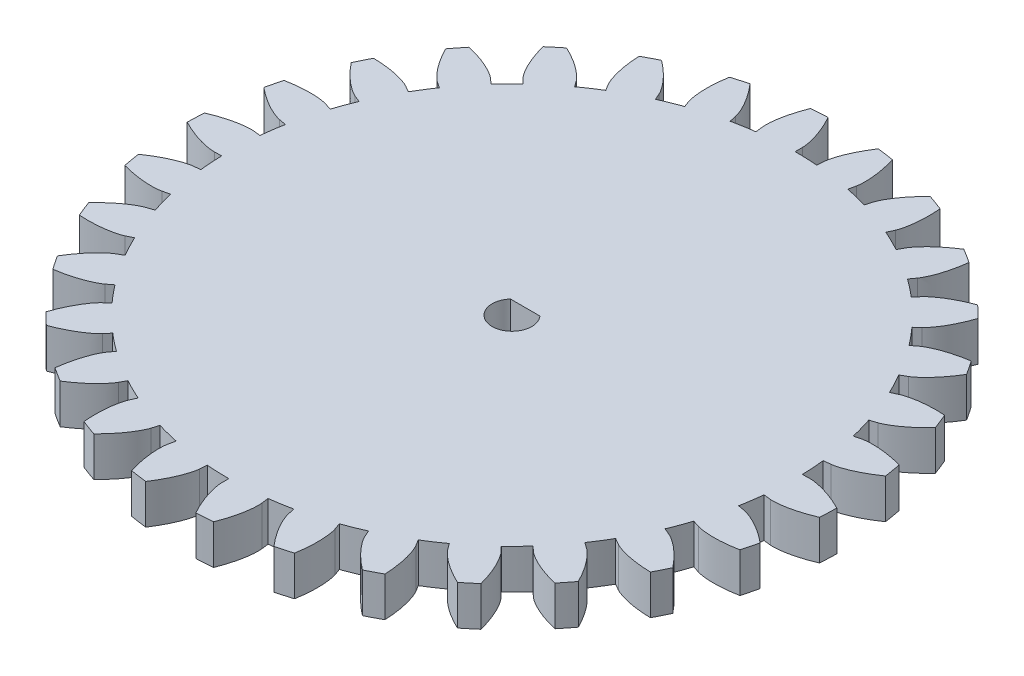
SolidWorks part; units mm, degrees
ref_plane "Front Plane" through (0, 0, 0) normal (0, 0, 1) x (1, 0, 0)
ref_plane "Top Plane" through (0, 0, 0) normal (0, 1, 0) x (1, 0, 0)
ref_plane "Right Plane" through (0, 0, 0) normal (1, 0, 0) x (0, 0, -1)
sketch "Reference attributes" plane through (0, 0, 0) normal (0, 1, 0) x (1, 0, 0)
  line L0 (0, 0) -> (30, 0) construction
  line L1 (0, -10) -> (1.56, -10) construction
  line L2 (0, 0) -> (28.9778, 7.7646) construction
  line L3 (0, 0) -> (28.1908, 10.2606) construction
  dimension "Teeth" = 30
  dimension "Module" = 1.56
  dimension "D2" = 10
  dimension "Helix Angle" = 15
  dimension "Pressure angle" = 20
sketch "Gear billet" plane through (0, 0, 0) normal (0, 1, 0) x (1, 0, 0)
  circle A0 centre (0, 0) radius 24.96
  dimension "OuterDi" = 49.92
extrude "Gear billet Extrude" add sketch "Gear billet" along normal blind 3
ref_plane "Opposite gear face" through (0, 3, 0) normal (0, 1, 0) x (1, 0, 0)
ref_point "Twist centre point top"
ref_point "Twist centre point bottom"
ref_axis "Axis" through (0, 3, 0) along (0, -1, 0)
sketch "Involute Profile" plane through (0, 3, 0) normal (0, 1, 0) x (1, 0, 0)
  line L0 (0, 0) -> (0, 21.9888) construction
  line L1 (0, 0) -> (1.7393, 21.9199) construction
  circle A0 centre (0, 0) radius 23.4
  circle A4 centre (0, 0) radius 21.9888 construction
  spline S0 degree 4 poles (0, 21.9888) (0, 22.0227) (-0.002, 22.0904) (-0.0183, 22.28) (-0.0768, 22.638) (-0.2134, 23.1773) (-0.4715, 23.897) (-0.8867, 24.788) (-1.4705, 25.7809) (-2.2091, 26.8084) (-3.0996, 27.8414) (-4.0685, 28.8009) (-5.1038, 29.688) (-6.2499, 30.5444) (-7.7363, 31.5083) (-9.5978, 32.5098) (-11.8594, 33.4668) (-14.465, 34.2773) (-17.1335, 34.8452) (-19.8405, 35.1813) (-22.5656, 35.2961) (-25.2912, 35.1997) (-27.663, 34.9395) (-29.6787, 34.5969) (-31.3427, 34.2349) (-32.4991, 33.942) (-33.4813, 33.6643) (-34.2972, 33.414) (-34.9416, 33.2053) (-35.5928, 32.9818) (-36.2216, 32.756) (-36.8226, 32.5279) (-37.3087, 32.3371) (-37.8607, 32.1112) (-38.2165, 31.9615) (-38.789, 31.7141) (-39.2308, 31.5139) (-39.7658, 31.2673) (-40.2388, 31.0393) (-40.7468, 30.7895) (-41.2252, 30.5448) (-41.5991, 30.3497) (-41.8363, 30.2223) (-41.9593, 30.1561) knots 0 0 0 0 0 0.002802 0.005604 0.015718 0.02996 0.048734 0.068727 0.096889 0.125051 0.153212 0.181374 0.209535 0.237696 0.271429 0.327752 0.384075 0.440398 0.496721 0.553044 0.609367 0.66569 0.722013 0.750174 0.778336 0.806497 0.820578 0.834659 0.84874 0.86282 0.876901 0.890982 0.900036 0.909091 0.920455 0.931818 0.943182 0.954545 0.965909 0.977273 0.988636 1 1 1 1 1 construction
  spline S1 degree 4 poles (0, 21.9888) (0, 22.0227) (-0.002, 22.0904) (-0.0183, 22.28) (-0.0768, 22.638) (-0.2134, 23.1773) (-0.4715, 23.897) (-0.8867, 24.788) (-1.4705, 25.7809) (-2.2091, 26.8084) (-3.0996, 27.8414) (-4.0685, 28.8009) (-5.1038, 29.688) (-6.2499, 30.5444) (-7.7363, 31.5083) (-9.5978, 32.5098) (-11.8594, 33.4668) (-14.465, 34.2773) (-17.1335, 34.8452) (-19.8405, 35.1813) (-22.5656, 35.2961) (-25.2912, 35.1997) (-27.663, 34.9395) (-29.6787, 34.5969) (-31.3427, 34.2349) (-32.4991, 33.942) (-33.4813, 33.6643) (-34.2972, 33.414) (-34.9416, 33.2053) (-35.5928, 32.9818) (-36.2216, 32.756) (-36.8226, 32.5279) (-37.3087, 32.3371) (-37.7167, 32.1701) (-37.9021, 32.0931) (-37.9939, 32.0546) knots 0 0 0 0 0 0.002802 0.005604 0.015718 0.02996 0.048734 0.068727 0.096889 0.125051 0.153212 0.181374 0.209535 0.237696 0.271429 0.327752 0.384075 0.440398 0.496721 0.553044 0.609367 0.66569 0.722013 0.750174 0.778336 0.806497 0.820578 0.834659 0.84874 0.86282 0.876901 0.890982 0.900036 0.909091 0.909091 0.909091 0.909091 0.909091
  spline S2 degree 4 poles (1.7393, 21.9199) (1.742, 21.9537) (1.7493, 22.0211) (1.7806, 22.2087) (1.8672, 22.561) (2.046, 23.0878) (2.3602, 23.7848) (2.8446, 24.6402) (3.5051, 25.5838) (4.3226, 26.5496) (5.2921, 27.509) (6.3339, 28.3888) (7.4361, 29.1913) (8.6463, 29.9544) (10.2043, 30.7977) (12.1392, 31.6487) (14.4694, 32.4239) (17.131, 33.0257) (19.836, 33.3808) (22.5612, 33.5017) (25.2867, 33.4006) (27.9962, 33.0889) (30.34, 32.6419) (32.3223, 32.141) (33.9524, 31.6485) (35.082, 31.2651) (36.0392, 30.9106) (36.8327, 30.5965) (37.4586, 30.3374) (38.0901, 30.0632) (38.699, 29.7884) (39.2801, 29.5134) (39.7496, 29.2848) (40.282, 29.0159) (40.6248, 28.8385) (41.176, 28.5466) (41.6005, 28.3121) (42.1144, 28.0239) (42.5679, 27.7593) (43.0545, 27.4701) (43.5121, 27.1883) (43.8694, 26.9642) (44.0957, 26.8185) (44.2131, 26.7428) knots 0 0 0 0 0 0.002802 0.005604 0.015718 0.02996 0.048734 0.068727 0.096889 0.125051 0.153212 0.181374 0.209535 0.237696 0.271429 0.327752 0.384075 0.440398 0.496721 0.553044 0.609367 0.66569 0.722013 0.750174 0.778336 0.806497 0.820578 0.834659 0.84874 0.86282 0.876901 0.890982 0.900036 0.909091 0.920455 0.931818 0.943182 0.954545 0.965909 0.977273 0.988636 1 1 1 1 1 construction
  spline S3 degree 4 poles (1.7393, 21.9199) (1.742, 21.9537) (1.7493, 22.0211) (1.7806, 22.2087) (1.8672, 22.561) (2.046, 23.0878) (2.3602, 23.7848) (2.8446, 24.6402) (3.5051, 25.5838) (4.3226, 26.5496) (5.2921, 27.509) (6.3339, 28.3888) (7.4361, 29.1913) (8.6463, 29.9544) (10.2043, 30.7977) (12.1392, 31.6487) (14.4694, 32.4239) (17.131, 33.0257) (19.836, 33.3808) (22.5612, 33.5017) (25.2867, 33.4006) (27.9962, 33.0889) (30.34, 32.6419) (32.3223, 32.141) (33.9524, 31.6485) (35.082, 31.2651) (36.0392, 30.9106) (36.8327, 30.5965) (37.4586, 30.3374) (38.0901, 30.0632) (38.699, 29.7884) (39.2801, 29.5134) (39.7496, 29.2848) (40.1431, 29.086) (40.3219, 28.9946) (40.4103, 28.9489) knots 0 0 0 0 0 0.002802 0.005604 0.015718 0.02996 0.048734 0.068727 0.096889 0.125051 0.153212 0.181374 0.209535 0.237696 0.271429 0.327752 0.384075 0.440398 0.496721 0.553044 0.609367 0.66569 0.722013 0.750174 0.778336 0.806497 0.820578 0.834659 0.84874 0.86282 0.876901 0.890982 0.900036 0.909091 0.909091 0.909091 0.909091 0.909091
  point P6 (-0.3003, 23.3981)
  point P11 (2.1501, 23.301)
  dimension "BaseDi" = 43.9776
  dimension "Adjusted Reference Diameter" = 46.8
  dimension "Reference Circumferential pitch" = 2.4504
sketch "Tooth profile" plane through (0, 3, 0) normal (0, 1, 0) x (1, 0, 0)
  line L0 (0, 0) -> (0, 21.9888) construction
  line L1 (0, 0) -> (1.7393, 21.9199) construction
  line L2 (0, 0) -> (0, 21.9888)
  line L3 (0, 0) -> (1.7393, 21.9199)
  line L4 (-0.2, -5.0491) -> (-0.2, 21.9888) construction
  line L5 (-0.2, -5.0491) -> (1.9386, 21.9041) construction
  circle A0 centre (0, 0) radius 24.96 construction
  circle A1 centre (0, 0) radius 24.96
  circle A2 centre (0, 0) radius 21.45
  spline S0 degree 1 poles (-0.2, 21.9888) (-37.9165, 31.8702) knots 0 0 1 1 construction
  spline S1 degree 4 poles (999.1982, -17.1121) (-36.277, 17.6441) (-0.8293, 18.6178) (0.2518, 20.6259) (-0.0768, 22.638) (-0.2134, 23.1773) (-0.4715, 23.897) (-0.8867, 24.788) (-1.4705, 25.7809) (-2.2091, 26.8084) (-3.0996, 27.8414) (-4.0685, 28.8009) (-5.1038, 29.688) (-6.2499, 30.5444) (-7.7363, 31.5083) (-9.5978, 32.5098) (-11.8594, 33.4668) (-14.465, 34.2773) (-17.1335, 34.8452) (-19.8405, 35.1813) (-22.5656, 35.2961) (-25.2912, 35.1997) (-27.663, 34.9395) (-29.6787, 34.5969) (-31.3427, 34.2349) (-32.4991, 33.942) (-33.4813, 33.6643) (-34.2972, 33.414) (-34.9416, 33.2053) (-35.5928, 32.9818) (-36.2216, 32.756) (-36.8226, 32.5279) (-38.6811, 31.7987) (-42.1779, 30.2496) (-10.1825, 43.4984) (-959.7925, -355.2431) knots -0.138436 -0.138436 -0.138436 -0.138436 -0.138436 0.002802 0.005604 0.015718 0.02996 0.048734 0.068727 0.096889 0.125051 0.153212 0.181374 0.209535 0.237696 0.271429 0.327752 0.384075 0.440398 0.496721 0.553044 0.609367 0.66569 0.722013 0.750174 0.778336 0.806497 0.820578 0.834659 0.84874 0.86282 0.876901 0.890982 0.900036 1.039722 1.039722 1.039722 1.039722 1.039722 only from (0, 21.9888) to (-37.9939, 32.0546) construction
  spline S2 degree 4 poles (-997.4211, 61.976) (37.5589, 14.7194) (2.2993, 18.4939) (1.3805, 20.5812) (1.8672, 22.561) (2.046, 23.0878) (2.3602, 23.7848) (2.8446, 24.6402) (3.5051, 25.5838) (4.3226, 26.5496) (5.2921, 27.509) (6.3339, 28.3888) (7.4361, 29.1913) (8.6463, 29.9544) (10.2043, 30.7977) (12.1392, 31.6487) (14.4694, 32.4239) (17.131, 33.0257) (19.836, 33.3808) (22.5612, 33.5017) (25.2867, 33.4006) (27.9962, 33.0889) (30.34, 32.6419) (32.3223, 32.141) (33.9524, 31.6485) (35.082, 31.2651) (36.0392, 30.9106) (36.8327, 30.5965) (37.4586, 30.3374) (38.0901, 30.0632) (38.699, 29.7884) (39.2801, 29.5134) (41.0751, 28.6395) (44.4385, 26.8186) (13.5912, 42.5567) (928.6863, -430.0476) knots -0.138436 -0.138436 -0.138436 -0.138436 -0.138436 0.002802 0.005604 0.015718 0.02996 0.048734 0.068727 0.096889 0.125051 0.153212 0.181374 0.209535 0.237696 0.271429 0.327752 0.384075 0.440398 0.496721 0.553044 0.609367 0.66569 0.722013 0.750174 0.778336 0.806497 0.820578 0.834659 0.84874 0.86282 0.876901 0.890982 0.900036 1.039722 1.039722 1.039722 1.039722 1.039722 only from (1.7393, 21.9199) to (40.4103, 28.9489) construction
  spline S3 degree 1 poles (1.9386, 21.9041) (40.3186, 28.7712) knots 0 0 1 1 construction
  spline S4 degree 4 poles (0, 21.9888) (0, 22.0227) (-0.002, 22.0904) (-0.0183, 22.28) (-0.0768, 22.638) (-0.2134, 23.1773) (-0.4715, 23.897) (-0.8867, 24.788) (-1.4705, 25.7809) (-2.2091, 26.8084) (-3.0996, 27.8414) (-4.0685, 28.8009) (-5.1038, 29.688) (-6.2499, 30.5444) (-7.7363, 31.5083) (-9.5978, 32.5098) (-11.8594, 33.4668) (-14.465, 34.2773) (-17.1335, 34.8452) (-19.8405, 35.1813) (-22.5656, 35.2961) (-25.2912, 35.1997) (-27.663, 34.9395) (-29.6787, 34.5969) (-31.3427, 34.2349) (-32.4991, 33.942) (-33.4813, 33.6643) (-34.2972, 33.414) (-34.9416, 33.2053) (-35.5928, 32.9818) (-36.2216, 32.756) (-36.8226, 32.5279) (-37.3087, 32.3371) (-37.7167, 32.1701) (-37.9021, 32.0931) (-37.9939, 32.0546) knots 0 0 0 0 0 0.002802 0.005604 0.015718 0.02996 0.048734 0.068727 0.096889 0.125051 0.153212 0.181374 0.209535 0.237696 0.271429 0.327752 0.384075 0.440398 0.496721 0.553044 0.609367 0.66569 0.722013 0.750174 0.778336 0.806497 0.820578 0.834659 0.84874 0.86282 0.876901 0.890982 0.900036 0.909091 0.909091 0.909091 0.909091 0.909091
  spline S5 degree 4 poles (1.7393, 21.9199) (1.742, 21.9537) (1.7493, 22.0211) (1.7806, 22.2087) (1.8672, 22.561) (2.046, 23.0878) (2.3602, 23.7848) (2.8446, 24.6402) (3.5051, 25.5838) (4.3226, 26.5496) (5.2921, 27.509) (6.3339, 28.3888) (7.4361, 29.1913) (8.6463, 29.9544) (10.2043, 30.7977) (12.1392, 31.6487) (14.4694, 32.4239) (17.131, 33.0257) (19.836, 33.3808) (22.5612, 33.5017) (25.2867, 33.4006) (27.9962, 33.0889) (30.34, 32.6419) (32.3223, 32.141) (33.9524, 31.6485) (35.082, 31.2651) (36.0392, 30.9106) (36.8327, 30.5965) (37.4586, 30.3374) (38.0901, 30.0632) (38.699, 29.7884) (39.2801, 29.5134) (39.7496, 29.2848) (40.1431, 29.086) (40.3219, 28.9946) (40.4103, 28.9489) knots 0 0 0 0 0 0.002802 0.005604 0.015718 0.02996 0.048734 0.068727 0.096889 0.125051 0.153212 0.181374 0.209535 0.237696 0.271429 0.327752 0.384075 0.440398 0.496721 0.553044 0.609367 0.66569 0.722013 0.750174 0.778336 0.806497 0.820578 0.834659 0.84874 0.86282 0.876901 0.890982 0.900036 0.909091 0.909091 0.909091 0.909091 0.909091
  spline S6 degree 3 poles (-37.9165, 31.8702) (-34.5637, 33.2771) (-29.2333, 34.7703) (-21.9373, 35.188) (-16.4816, 34.6386) (-11.2068, 33.1415) (-7.1485, 31.0333) (-4.2854, 28.7886) (-2.4032, 26.8185) (-1.144, 24.9283) (-0.5176, 23.4861) (-0.2764, 22.622) (-0.2, 22.203) (-0.2, 21.9888) knots 0 0 0 0 0.227273 0.340909 0.454545 0.568182 0.681818 0.738636 0.795455 0.852273 0.880682 0.894886 0.909091 0.909091 0.909091 0.909091 construction
  spline S7 degree 3 poles (1.9386, 21.9041) (1.9556, 22.1176) (2.0649, 22.5293) (2.3737, 23.3716) (3.1122, 24.7598) (4.5169, 26.5444) (6.5491, 28.3595) (9.5808, 30.3707) (13.7931, 32.1512) (19.1698, 33.2264) (24.6519, 33.3426) (31.892, 32.3491) (37.0876, 30.439) (40.3186, 28.7712) knots 0 0 0 0 0.014205 0.028409 0.056818 0.113636 0.170455 0.227273 0.340909 0.454545 0.568182 0.681818 0.909091 0.909091 0.909091 0.909091 construction
  dimension "RootDi" = 42.9
  dimension "Offset" = 0.2
extrude "Cut tooth profile" cut sketch "Tooth profile" against normal up to next
sketch "Tooth profile OFFSET" plane through (0, 3, 0) normal (0, 1, 0) x (1, 0, 0)
  line L4 (-0.1, -2.5246) -> (-0.1, 21.9888)
  line L5 (1.839, 21.912) -> (-0.1, -2.5246)
  line L6 (-0.1, -2.5246) -> (-0.1, 21.9888)
  line L7 (1.839, 21.912) -> (-0.1, -2.5246)
  circle A3 centre (0, 0) radius 24.96 construction
  circle A4 centre (0, 0) radius 24.96
  circle A6 centre (0, 0) radius 21.35
  circle A7 centre (0, 0) radius 21.35
  spline S4 degree 3 poles (1814.9164, -893.4497) (11.2099, 41.5431) (47.43, 25.2825) (39.9677, 29.0624) (39.857, 29.118) (39.5391, 29.276) (39.3439, 29.3707) (38.9333, 29.5665) (38.7217, 29.6655) (38.306, 29.8557) (38.0998, 29.9479) (37.053, 30.4066) (36.203, 30.7469) (33.6257, 31.6798) (31.8646, 32.1874) (28.2886, 32.9442) (26.4731, 33.1936) (22.8249, 33.4041) (20.9921, 33.3652) (17.3608, 32.9668) (15.562, 32.6072) (12.0726, 31.5326) (10.3808, 30.8175) (8.0112, 29.4496) (7.2497, 28.9445) (5.8069, 27.8305) (5.1252, 27.2218) (3.8784, 25.8951) (3.3115, 25.1772) (2.6029, 24.0143) (2.3903, 23.6123) (2.1256, 22.9877) (2.0464, 22.776) (1.9476, 22.4534) (1.918, 22.3451) (0.4034, 15.6952) (12.5067, 9.1011) (1949.2716, 476.354) knots -0.54262 -0.54262 -0.54262 -0.54262 0.007812 0.007812 0.015625 0.015625 0.03125 0.03125 0.046875 0.046875 0.0625 0.0625 0.125 0.125 0.25 0.25 0.375 0.375 0.5 0.5 0.625 0.625 0.75 0.75 0.8125 0.8125 0.875 0.875 0.9375 0.9375 0.96875 0.96875 0.984375 0.984375 0.992187 0.992187 1.461818 1.461818 1.461818 1.461818 only from (40.3645, 28.8601) to (1.839, 21.912)
  spline S5 degree 3 poles (-1905.5571, 629.0682) (-11.748, 10.0617) (0.8394, 15.6778) (-0.1445, 22.4268) (-0.1655, 22.5371) (-0.2385, 22.8665) (-0.3007, 23.0838) (-0.5151, 23.7274) (-0.6952, 24.1449) (-1.3097, 25.3602) (-1.818, 26.1208) (-2.956, 27.5419) (-3.5873, 28.2027) (-4.9375, 29.4272) (-5.6567, 29.991) (-7.9107, 31.542) (-9.5406, 32.3887) (-12.9341, 33.736) (-14.6989, 34.2367) (-18.2872, 34.9211) (-20.1112, 35.1048) (-23.7646, 35.1836) (-25.5942, 35.0786) (-29.2188, 34.607) (-31.0145, 34.2403) (-33.6576, 33.5142) (-34.5318, 33.2422) (-35.6116, 32.8677) (-35.8244, 32.7921) (-36.2539, 32.6354) (-36.4727, 32.5534) (-36.8975, 32.3907) (-37.0995, 32.3118) (-37.429, 32.1793) (-37.5437, 32.1327) (-45.2816, 28.9549) (-7.889, 42.2995) (-1879.8826, -747.087) knots -0.461823 -0.461823 -0.461823 -0.461823 0.007812 0.007812 0.015625 0.015625 0.03125 0.03125 0.0625 0.0625 0.125 0.125 0.1875 0.1875 0.25 0.25 0.375 0.375 0.5 0.5 0.625 0.625 0.75 0.75 0.875 0.875 0.9375 0.9375 0.953125 0.953125 0.96875 0.96875 0.984375 0.984375 0.992188 0.992188 1.542618 1.542618 1.542618 1.542618 only from (-0.1, 21.9888) to (-37.9552, 31.9624)
  spline S6 degree 3 poles (40.3645, 28.8601) (40.2722, 28.9077) (40.1765, 28.9566) (39.9677, 29.0624) (39.857, 29.118) (39.5391, 29.276) (39.3439, 29.3707) (38.9333, 29.5665) (38.7217, 29.6655) (38.306, 29.8557) (38.0998, 29.9479) (37.053, 30.4066) (36.203, 30.7469) (33.6257, 31.6798) (31.8646, 32.1874) (28.2886, 32.9442) (26.4731, 33.1936) (22.8249, 33.4041) (20.9921, 33.3652) (17.3608, 32.9668) (15.562, 32.6072) (12.0726, 31.5326) (10.3808, 30.8175) (8.0112, 29.4496) (7.2497, 28.9445) (5.8069, 27.8305) (5.1252, 27.2218) (3.8784, 25.8951) (3.3115, 25.1772) (2.6029, 24.0143) (2.3903, 23.6123) (2.1256, 22.9877) (2.0464, 22.776) (1.9476, 22.4534) (1.918, 22.3451) (1.8684, 22.1275) (1.8474, 22.0187) (1.839, 21.912) knots 0 0 0 0 0.007812 0.007812 0.015625 0.015625 0.03125 0.03125 0.046875 0.046875 0.0625 0.0625 0.125 0.125 0.25 0.25 0.375 0.375 0.5 0.5 0.625 0.625 0.75 0.75 0.8125 0.8125 0.875 0.875 0.9375 0.9375 0.96875 0.96875 0.984375 0.984375 0.992187 0.992187 1 1 1 1
  spline S7 degree 3 poles (-0.1, 21.9888) (-0.1, 22.0958) (-0.1123, 22.206) (-0.1445, 22.4268) (-0.1655, 22.5371) (-0.2385, 22.8665) (-0.3007, 23.0838) (-0.5151, 23.7274) (-0.6952, 24.1449) (-1.3097, 25.3602) (-1.818, 26.1208) (-2.956, 27.5419) (-3.5873, 28.2027) (-4.9375, 29.4272) (-5.6567, 29.991) (-7.9107, 31.542) (-9.5406, 32.3887) (-12.9341, 33.736) (-14.6989, 34.2367) (-18.2872, 34.9211) (-20.1112, 35.1048) (-23.7646, 35.1836) (-25.5942, 35.0786) (-29.2188, 34.607) (-31.0145, 34.2403) (-33.6576, 33.5142) (-34.5318, 33.2422) (-35.6116, 32.8677) (-35.8244, 32.7921) (-36.2539, 32.6354) (-36.4727, 32.5534) (-36.8975, 32.3907) (-37.0995, 32.3118) (-37.429, 32.1793) (-37.5437, 32.1327) (-37.7603, 32.0437) (-37.8595, 32.0026) (-37.9552, 31.9624) knots 0 0 0 0 0.007812 0.007812 0.015625 0.015625 0.03125 0.03125 0.0625 0.0625 0.125 0.125 0.1875 0.1875 0.25 0.25 0.375 0.375 0.5 0.5 0.625 0.625 0.75 0.75 0.875 0.875 0.9375 0.9375 0.953125 0.953125 0.96875 0.96875 0.984375 0.984375 0.992188 0.992188 1 1 1 1
  line M3 (0, 21.45) -> (0, 21.9888)
  spline M4 degree 4 poles (0, 21.9888) (0, 22.0227) (-0.002, 22.0904) (-0.0183, 22.28) (-0.0768, 22.638) (-0.2134, 23.1773) (-0.4715, 23.897) (-0.8867, 24.788) (-1.4705, 25.7809) (-2.2091, 26.8084) (-3.0996, 27.8414) (-4.0685, 28.8009) (-5.1038, 29.688) (-6.2499, 30.5444) (-7.7363, 31.5083) (-9.5978, 32.5098) (-11.8594, 33.4668) (-14.465, 34.2773) (-17.1335, 34.8452) (-19.8405, 35.1813) (-22.5656, 35.2961) (-25.2912, 35.1997) (-27.663, 34.9395) (-29.6787, 34.5969) (-31.3427, 34.2349) (-32.4991, 33.942) (-33.4813, 33.6643) (-34.2972, 33.414) (-34.9416, 33.2053) (-35.5928, 32.9818) (-36.2216, 32.756) (-36.8226, 32.5279) (-37.3087, 32.3371) (-37.7167, 32.1701) (-37.9021, 32.0931) (-37.9939, 32.0546) knots 0 0 0 0 0 0.002802 0.005604 0.015718 0.02996 0.048734 0.068727 0.096889 0.125051 0.153212 0.181374 0.209535 0.237696 0.271429 0.327752 0.384075 0.440398 0.496721 0.553044 0.609367 0.66569 0.722013 0.750174 0.778336 0.806497 0.820578 0.834659 0.84874 0.86282 0.876901 0.890982 0.900036 0.909091 0.909091 0.909091 0.909091 0.909091 only from (0, 21.9888) to (-0.9929, 24.9402)
  arc M5 (-0.9929, 24.9402) -> (2.9625, 24.7836) centre (0, 0) ccw
  spline M6 degree 4 poles (40.4103, 28.9489) (40.3219, 28.9946) (40.1431, 29.086) (39.7496, 29.2848) (39.2801, 29.5134) (38.699, 29.7884) (38.0901, 30.0632) (37.4586, 30.3374) (36.8327, 30.5965) (36.0392, 30.9106) (35.082, 31.2651) (33.9524, 31.6485) (32.3223, 32.141) (30.34, 32.6419) (27.9962, 33.0889) (25.2867, 33.4006) (22.5612, 33.5017) (19.836, 33.3808) (17.131, 33.0257) (14.4694, 32.4239) (12.1392, 31.6487) (10.2043, 30.7977) (8.6463, 29.9544) (7.4361, 29.1913) (6.3339, 28.3888) (5.2921, 27.509) (4.3226, 26.5496) (3.5051, 25.5838) (2.8446, 24.6402) (2.3602, 23.7848) (2.046, 23.0878) (1.8672, 22.561) (1.7806, 22.2087) (1.7493, 22.0211) (1.742, 21.9537) (1.7393, 21.9199) knots 0 0 0 0 0 0.009054 0.018109 0.03219 0.04627 0.060351 0.074432 0.088513 0.102594 0.130755 0.158916 0.187078 0.243401 0.299724 0.356047 0.41237 0.468693 0.525016 0.581339 0.637662 0.671395 0.699556 0.727717 0.755879 0.78404 0.812202 0.840364 0.860357 0.879131 0.893373 0.903487 0.906289 0.909091 0.909091 0.909091 0.909091 0.909091 only from (2.9625, 24.7836) to (1.7393, 21.9199)
  line M7 (1.7393, 21.9199) -> (1.6967, 21.3828)
  arc M8 (1.6967, 21.3828) -> (0, 21.45) centre (0, 0) ccw
  dimension "Offset" = 0.1
  dimension "D2" = 0.1
extrude "Cut Tooth profile OFFSET" [suppressed] cut sketch "Tooth profile OFFSET" against normal up to surface (10 mm away) contours S7 L6 A7 L7 S6 A4 M6 M7 M8 M3 M4 M5
sketch "Tangent meshing reference" plane through (0, 3, 0) normal (0, 1, 0) x (1, 0, 0)
  circle A0 centre (0, 0) radius 23.4 construction
  circle A1 centre (0, 0) radius 23.4
sketch "Gear ratio reference" plane through (0, 3, 0) normal (0, 1, 0) x (1, 0, 0)
  circle A0 centre (0, 0) radius 23.4
  dimension "Reference diameter" = 46.8
pattern_circular "Duplicate teeth" count 30 over 360 about axis through (0, 3, 0) along (0, -1, 0) of "Cut tooth profile"
other "Twist Left" [suppressed] parameters "D0"=1.968
other "Twist Right" [suppressed] parameters "D0"=1.968
mirror "Herringbone Mirror" [suppressed] about plane through (0, 3, 0) normal (0, 1, 0)
sketch "Sketch1" plane through (0, 3, 0) normal (0, 1, 0) x (1, 0, 0)
  line L0 (-1.118, 1) -> (1.118, 1)
  arc A0 (-1.118, 1) -> (1.118, 1) centre (0, 0) ccw
  dimension "D1" = 3
  dimension "D2" = 2.5
extrude "Cut-Extrude1" cut sketch "Sketch1" against normal through all
equation "\"D1@Duplicate teeth\"=\"Teeth@Reference attributes\""
equation "\"twist\"= \"suppressed\""
equation "\"D2@Tooth profile OFFSET\"=\"Offset@Tooth profile OFFSET\""
